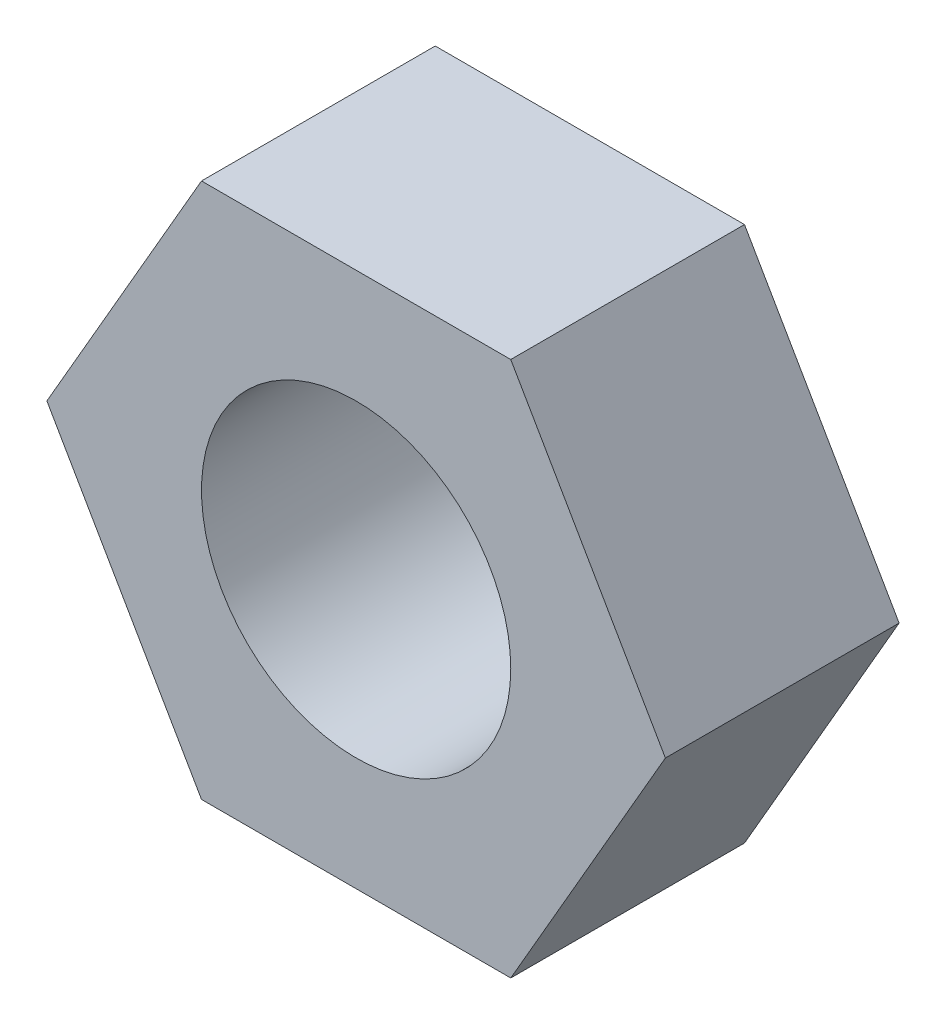
SolidWorks part; units mm, degrees
ref_plane "前视基准面" through (0, 0, 0) normal (0, 0, 1) x (1, 0, 0)
ref_plane "上视基准面" through (0, 0, 0) normal (0, 1, 0) x (1, 0, 0)
ref_plane "右视基准面" through (0, 0, 0) normal (1, 0, 0) x (0, 0, -1)
sketch "草图1" plane through (0, 0, 0) normal (0, 0, 1) x (1, 0, 0)
  line L1 (3.1754, 0) -> (1.5877, 2.75)
  line L2 (1.5877, 2.75) -> (-1.5877, 2.75)
  line L3 (-1.5877, 2.75) -> (-3.1754, 0)
  line L4 (-3.1754, 0) -> (-1.5877, -2.75)
  line L5 (-1.5877, -2.75) -> (1.5877, -2.75)
  line L6 (1.5877, -2.75) -> (3.1754, 0)
  circle A0 centre (0, 0) radius 2.75 construction
  circle A1 centre (0, 0) radius 1.5877
  dimension "D1" = 3.1754
  dimension "D2" = 5.5
extrude "M3螺母_对边5.5_厚2.4_牙型简化" add sketch "草图1" along normal blind 2.4
